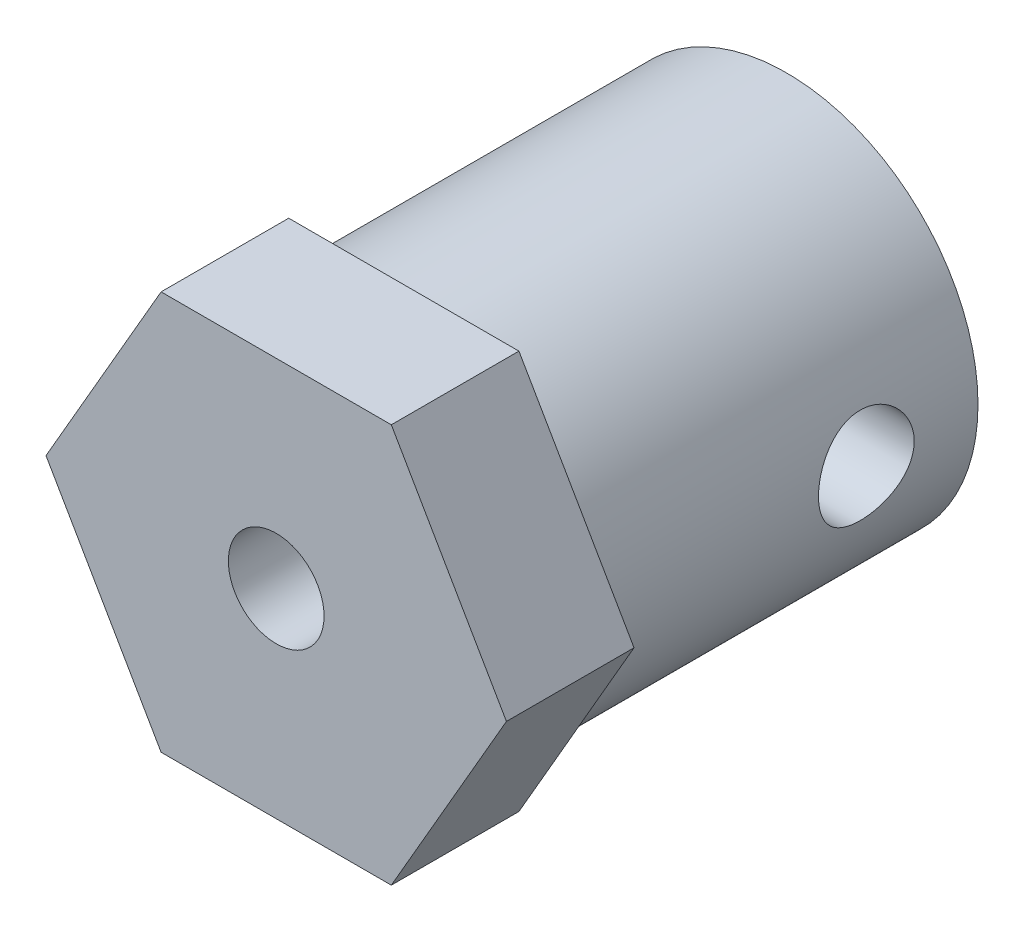
SolidWorks part; units mm, degrees
ref_plane "Alzado" through (0, 0, 0) normal (0, 0, 1) x (1, 0, 0)
ref_plane "Planta" through (0, 0, 0) normal (0, 1, 0) x (1, 0, 0)
ref_plane "Vista lateral" through (0, 0, 0) normal (1, 0, 0) x (0, 0, -1)
sketch "Croquis2" plane through (0, 0, 0) normal (0, 0, 1) x (1, 0, 0)
  line L1 (3.6084, 6.25) -> (-3.6084, 6.25)
  line L2 (-3.6084, 6.25) -> (-7.2169, 0)
  line L3 (-7.2169, 0) -> (-3.6084, -6.25)
  line L4 (-3.6084, -6.25) -> (3.6084, -6.25)
  line L5 (3.6084, -6.25) -> (7.2169, 0)
  line L6 (7.2169, 0) -> (3.6084, 6.25)
  circle A0 centre (0, 0) radius 6.25 construction
  circle A1 centre (0, 0) radius 1.5
  dimension "D1" = 3
  dimension "D2" = 12.5
extrude "Saliente-Extruir1" add sketch "Croquis2" along normal blind 4
sketch "Croquis3" plane through (0, 0, 0) normal (0, 0, -1) x (-1, 0, 0)
  circle A0 centre (0, 0) radius 6
  circle A1 centre (0, 0) radius 3.175
  dimension "D1" = 12
  dimension "D2" = 6.35
extrude "Saliente-Extruir2" add sketch "Croquis3" along normal blind 12 contours A0 | A1
sketch "Croquis4" plane through (0, 0, 0) normal (1, 0, 0) x (0, 0, -1)
  line L0 (0, 0) -> (16.2588, 0) construction
  circle A0 centre (8.5, 0) radius 1.5
  dimension "D2" = 3
  dimension "D1" = 8.5
extrude "Cortar-Extruir1" cut sketch "Croquis4" along normal blind 10
